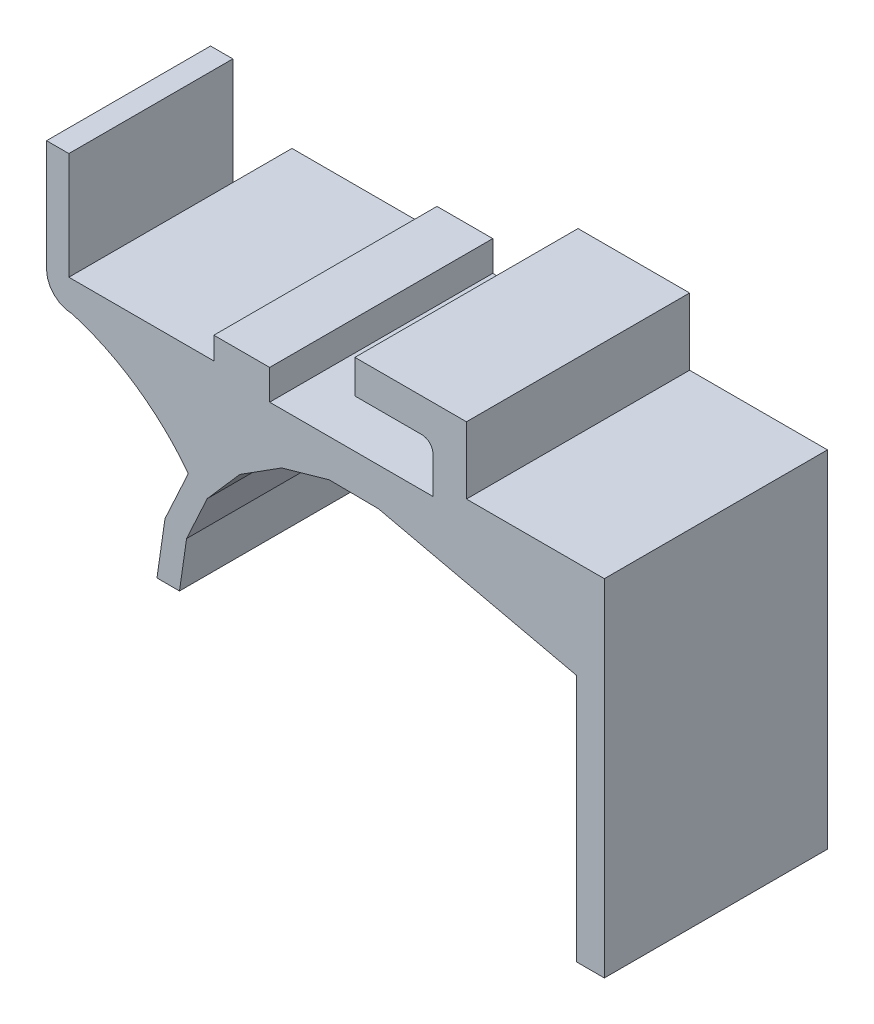
SolidWorks part; units mm, degrees
ref_plane "Alzado" through (0, 0, 0) normal (0, 0, 1) x (1, 0, 0)
ref_plane "Planta" through (0, 0, 0) normal (0, 1, 0) x (1, 0, 0)
ref_plane "Vista lateral" through (0, 0, 0) normal (1, 0, 0) x (0, 0, -1)
sketch "Croquis2" plane through (0, 0, 0) normal (0, 0, 1) x (1, 0, 0)
  line L0 (-51.9511, -1.694) -> (-49.9511, -1.694)
  line L1 (-49.9511, -1.694) -> (-51.9511, -1.694)
  line L2 (-1.9511, -10.694) -> (-1.9511, -41.694)
  line L3 (-1.9511, -41.694) -> (-51.9511, -41.694) construction
  line L4 (-51.9511, -1.694) -> (-51.9511, -41.694) construction
  line L5 (-49.9511, -1.694) -> (-49.9511, -11.294)
  line L6 (-49.9511, -11.294) -> (-36.9511, -11.294)
  line L7 (-36.9511, -11.294) -> (-36.9511, -9.294)
  line L8 (-36.9511, -9.294) -> (-31.9511, -9.294)
  line L9 (-31.9511, -9.294) -> (-31.9511, -11.994)
  line L10 (-31.9511, -11.994) -> (-17.3111, -11.994)
  line L11 (-17.3111, -11.994) -> (-17.3111, -7.694)
  line L12 (-17.3111, -7.694) -> (-24.3111, -7.694)
  line L13 (-24.3111, -7.694) -> (-24.3111, -4.694)
  line L14 (-24.3111, -4.694) -> (-14.3111, -4.694)
  line L15 (-14.3111, -4.694) -> (-14.3111, -10.694)
  line L16 (-14.3111, -10.694) -> (-1.9511, -10.694)
  line L17 (-1.9511, -41.694) -> (-4.5642, -41.694)
  line L18 (-4.5642, -41.694) -> (-4.5642, -19.454)
  line L19 (-4.5642, -19.454) -> (-22.3242, -19.454) construction
  line L20 (-22.3242, -41.694) -> (-22.3242, -15.394) construction
  line L21 (-4.5642, -19.454) -> (-22.3242, -15.394)
  line L22 (-42.1842, -30.694) -> (-40.1642, -30.694)
  line L23 (-22.3242, -15.394) -> (-26.7442, -15.394) construction
  line L24 (-42.1842, -41.694) -> (-42.1842, -30.694) construction
  line L25 (-40.1642, -41.694) -> (-40.1642, -30.694) construction
  line L26 (-26.7442, -15.394) -> (-26.7442, -15.354)
  line L27 (-22.3242, -15.394) -> (-26.7442, -15.354)
  line L28 (-40.1642, -30.694) -> (-26.7442, -15.354) construction
  arc A0 (-40.1642, -30.694) -> (-26.7442, -15.354) centre (-26.4173, -29.1801) cw
  point P28 (0, 0)
  point P29 (0, 0)
  point P30 (0, 0)
  dimension "D1" = 2
  dimension "D2" = 50
  dimension "D3" = 40
  dimension "D4" = 9.6
  dimension "D5" = 13
  dimension "D6" = 2
  dimension "D7" = 5
  dimension "D8" = 2.7
  dimension "D9" = 14.64
  dimension "D10" = 4.3
  dimension "D11" = 3
  dimension "D12" = 10
  dimension "D13" = 6
  dimension "D14" = 12.36
  dimension "D15" = 22.24
  dimension "D16" = 17.76
  dimension "D17" = 26.3
  dimension "D18" = 35.6
  dimension "D19" = 2.02
  dimension "D20" = 11
  dimension "D21" = 4.42
  dimension "D22" = 0.04
sketch "Croquis3" plane through (0, 0, 0) normal (0, 0, 1) x (1, 0, 0)
  line L0 (-51.9527, -11.691) -> (-51.8744, -12.2863)
  line L1 (-51.8744, -12.2863) -> (-51.6446, -12.841)
  line L2 (-51.6446, -12.841) -> (-51.2791, -13.3174)
  line L3 (-51.2791, -13.3174) -> (-50.8027, -13.6829)
  line L4 (-50.248, -13.9127) -> (-49.6525, -13.9915)
  line L5 (-50.8027, -13.6829) -> (-50.248, -13.9127)
  line L6 (-49.6525, -13.9915) -> (-48.6343, -14.3253)
  line L7 (-48.6343, -14.3253) -> (-47.6349, -14.7118)
  line L8 (-47.6349, -14.7118) -> (-46.6571, -15.1501)
  line L9 (-46.6571, -15.1501) -> (-45.7035, -15.6388)
  line L10 (-45.7035, -15.6388) -> (-44.7768, -16.1766)
  line L11 (-44.7768, -16.1766) -> (-43.8794, -16.7622)
  line L12 (-43.8794, -16.7622) -> (-43.0138, -17.3938)
  line L13 (-43.0138, -17.3938) -> (-42.1824, -18.0698)
  line L14 (-42.1824, -18.0698) -> (-41.3875, -18.7883)
  line L15 (-40.6312, -19.5474) -> (-39.9156, -20.3449)
  line L16 (-41.3875, -18.7883) -> (-40.6312, -19.5474)
  line L17 (-39.2426, -21.1787) -> (-39.9156, -20.3449)
  line L18 (-41.3372, -25.7329) -> (-39.2426, -21.1787)
  line L19 (-42.055, -30.694) -> (-41.3372, -25.7329)
  line L20 (-40.0342, -30.694) -> (-42.055, -30.694)
  line L21 (-40.0342, -30.694) -> (-39.3992, -26.3057)
  line L22 (-37.5465, -22.2773) -> (-39.3992, -26.3057)
  line L23 (-34.6279, -18.9394) -> (-37.5465, -22.2773)
  line L24 (-30.8828, -16.5656) -> (-34.6279, -18.9394)
  line L25 (-26.8105, -15.4054) -> (-30.8828, -16.5656)
  line L26 (-22.1958, -15.3943) -> (-26.6185, -15.3507)
  line L27 (-4.4311, -19.4548) -> (-22.1958, -15.3943)
  line L28 (-4.4311, -41.694) -> (-4.4311, -19.4548)
  line L29 (-1.9511, -41.694) -> (-4.4311, -41.694)
  line L30 (-1.9511, -41.694) -> (-1.9511, -10.694)
  line L31 (-14.3115, -10.694) -> (-1.9511, -10.694)
  line L32 (-14.3115, -10.694) -> (-14.3115, -4.694)
  line L33 (-24.3115, -4.694) -> (-14.3115, -4.694)
  line L34 (-24.3115, -7.694) -> (-24.3115, -4.694)
  line L35 (-18.3115, -7.694) -> (-24.3115, -7.694)
  line L36 (-17.3115, -11.994) -> (-17.3115, -8.694)
  line L37 (-17.3115, -11.994) -> (-31.9525, -11.994)
  line L38 (-31.9525, -9.294) -> (-31.9525, -11.994)
  line L39 (-31.9525, -9.294) -> (-36.9525, -9.294)
  line L40 (-36.9525, -9.294) -> (-36.9525, -11.294)
  line L41 (-36.9525, -11.294) -> (-49.9525, -11.294)
  line L42 (-49.9525, -1.694) -> (-49.9525, -11.294)
  line L43 (-51.9515, -1.6938) -> (-49.9525, -1.694)
  line L44 (-51.9515, -1.6938) -> (-51.9527, -11.691)
  line L52 (-17.3115, -8.694) -> (-17.3455, -8.4351)
  line L54 (-17.4454, -8.194) -> (-17.3455, -8.4351)
  line L55 (-17.6044, -7.9869) -> (-17.4454, -8.194)
  line L56 (-17.8115, -7.8279) -> (-17.6044, -7.9869)
  line L57 (-18.0527, -7.728) -> (-17.8115, -7.8279)
  line L58 (-18.3115, -7.694) -> (-18.0527, -7.728)
  line L59 (-26.6185, -15.3507) -> (-26.8105, -15.4054)
  arc A4 (-18.3115, -7.694) -> (-17.3115, -8.694) centre (-18.3115, -8.694) cw
  dimension "D1" = 2.48
extrude "Saliente-Extruir1" add sketch "Croquis3" along normal blind 20 contours L35 A4 L36 L37 L38 L39 L40 L41 L42 L43 L44 L0 L1 L2 L3 L5 L4 L6 L7 L8 L9 L10 L11 L12 L13 L14 L16 L15 L17 L18 L19 L20 L21 L22 L23 L24 L25 L59 L26 L27 L28 L29 L30 L31 L32 L33
sketch "Croquis4" plane through (0, 0, 0) normal (0, 0, -1) x (-1, 0, 0)
  line L0 (49.9525, -11.294) -> (49.9503, -13.9521)
  line L1 (50.248, -13.9127) -> (49.6525, -13.9915) construction
  line L2 (49.9525, -1.694) -> (49.9525, -11.294) construction
  line L3 (51.9515, -1.6938) -> (49.9525, -1.694) construction
  line L4 (51.9515, -1.6938) -> (51.9527, -11.691) construction
  line L5 (51.9527, -11.691) -> (51.8744, -12.2863) construction
  line L6 (51.8744, -12.2863) -> (51.6446, -12.841) construction
  line L7 (51.6446, -12.841) -> (51.2791, -13.3174) construction
  line L8 (51.2791, -13.3174) -> (50.8027, -13.6829) construction
  line L9 (50.8027, -13.6829) -> (50.248, -13.9127) construction
  line L10 (49.9525, -1.694) -> (49.9525, -11.294)
  line L11 (51.9515, -1.6938) -> (49.9525, -1.694)
  line L12 (51.9515, -1.6938) -> (51.9527, -11.691)
  line L13 (51.9527, -11.691) -> (51.8744, -12.2863)
  line L14 (51.8744, -12.2863) -> (51.6446, -12.841)
  line L15 (51.6446, -12.841) -> (51.2791, -13.3174)
  line L16 (51.2791, -13.3174) -> (50.8027, -13.6829)
  line L17 (50.8027, -13.6829) -> (50.248, -13.9127)
  line L18 (50.248, -13.9127) -> (49.9503, -13.9521)
extrude "Cortar-Extruir1" cut sketch "Croquis4" against normal blind 5.3
